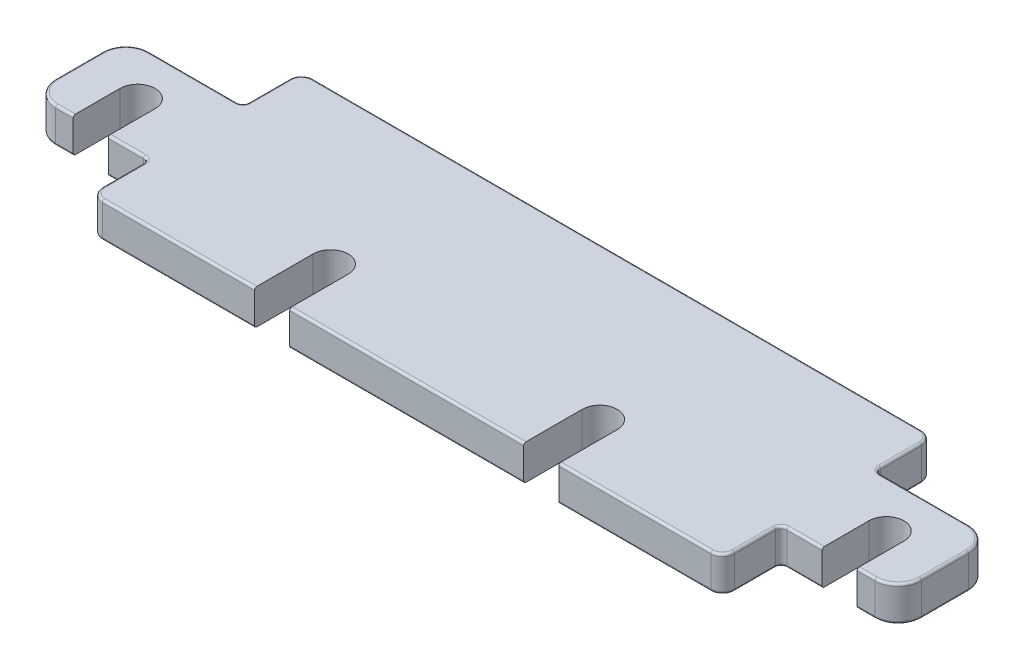
SolidWorks part; units mm, degrees
ref_plane "Front Plane" through (0, 0, 0) normal (0, 0, 1) x (1, 0, 0)
ref_plane "Top Plane" through (0, 0, 0) normal (0, 1, 0) x (1, 0, 0)
ref_plane "Right Plane" through (0, 0, 0) normal (1, 0, 0) x (0, 0, -1)
sketch "Sketch1" plane through (0, 0, 0) normal (0, 1, 0) x (1, 0, 0)
  line L0 (0, 0) -> (0, 18) construction
  line L1 (-10, 5) -> (-10, 0)
  line L2 (-10, 0) -> (10, 0)
  line L3 (-13, 5) -> (-13, 0)
  line L4 (-13, 0) -> (-26, 0)
  line L5 (-27, 1) -> (-27, 4.5)
  line L6 (-27.5, 5) -> (-30.5, 5)
  line L7 (-37, 7) -> (-37, 11)
  line L8 (-35, 13) -> (-27.5, 13)
  line L9 (-27, 13.5) -> (-27, 17)
  line L10 (-26, 18) -> (26, 18)
  line L11 (-33.5, 9) -> (-33.5, 5)
  line L12 (-30.5, 9) -> (-30.5, 5)
  line L13 (-33.5, 5) -> (-35, 5)
  line L14 (33.5, 5) -> (35, 5)
  line L15 (30.5, 9) -> (30.5, 5)
  line L16 (33.5, 9) -> (33.5, 5)
  line L17 (27, 13.5) -> (27, 17)
  line L18 (35, 13) -> (27.5, 13)
  line L19 (37, 7) -> (37, 11)
  line L20 (27.5, 5) -> (30.5, 5)
  line L21 (27, 1) -> (27, 4.5)
  line L22 (13, 0) -> (26, 0)
  line L23 (13, 5) -> (13, 0)
  line L24 (10, 5) -> (10, 0)
  arc A0 (-10, 5) -> (-13, 5) centre (-11.5, 5) ccw
  arc A1 (-30.5, 9) -> (-33.5, 9) centre (-32, 9) ccw
  arc A2 (-26, 0) -> (-27, 1) centre (-26, 1) cw
  arc A3 (-27, 17) -> (-26, 18) centre (-26, 17) cw
  arc A4 (-35, 5) -> (-37, 7) centre (-35, 7) cw
  arc A5 (-37, 11) -> (-35, 13) centre (-35, 11) cw
  arc A6 (-27, 4.5) -> (-27.5, 5) centre (-27.5, 4.5) ccw
  arc A7 (-27.5, 13) -> (-27, 13.5) centre (-27.5, 13.5) ccw
  arc A8 (27.5, 13) -> (27, 13.5) centre (27.5, 13.5) cw
  arc A9 (27, 4.5) -> (27.5, 5) centre (27.5, 4.5) cw
  arc A10 (37, 11) -> (35, 13) centre (35, 11) ccw
  arc A11 (35, 5) -> (37, 7) centre (35, 7) ccw
  arc A12 (27, 17) -> (26, 18) centre (26, 17) ccw
  arc A13 (26, 0) -> (27, 1) centre (26, 1) ccw
  arc A14 (30.5, 9) -> (33.5, 9) centre (32, 9) cw
  arc A15 (10, 5) -> (13, 5) centre (11.5, 5) cw
  point P21 (-27, 0)
  point P26 (-37, 5)
  point P29 (-37, 13)
  point P32 (-27, 5)
  point P63 (27, 5)
  point P64 (37, 13)
  point P65 (37, 5)
  point P66 (27, 0)
  dimension "D1" = 3
  dimension "D9" = 3
  dimension "D12" = 1
  dimension "D13" = 2
  dimension "D14" = 0.5
  dimension "D2" = 10
  dimension "D3" = 5
  dimension "D4" = 27
  dimension "D5" = 10
  dimension "D6" = 8
  dimension "D7" = 18
  dimension "D8" = 5
  dimension "D10" = 5
  dimension "D11" = 4
extrude "Boss-Extrude1" add sketch "Sketch1" along normal blind 3
fillet "Fillet1" radius 0.2 56 edges at (29, 0, -5) (27.1464, 0, -4.8536) (27, 0, -2.75) (26.7071, 0, -0.2929) (29, 3, -5) (27.1464, 3, -4.8536) (27, 3, -2.75) (26.7071, 3, -0.2929) (-29, 0, -5) (-27.1464, 0, -4.8536) (-27, 0, -2.75) (-26.7071, 0, -0.2929) (-19.5, 3, 0) (-26.7071, 3, -0.2929) (-27, 3, -2.75) (-27.1464, 3, -4.8536) (34.25, 0, -5) (36.4142, 0, -5.5858) (37, 0, -9) (36.4142, 0, -12.4142) (31.25, 0, -13) (27.1464, 0, -13.1464) (27, 0, -15.25) (26.7071, 0, -17.7071) (0, 0, -18) (-26.7071, 0, -17.7071) (-27, 0, -15.25) (-27.1464, 0, -13.1464) (-31.25, 0, -13) (-36.4142, 0, -12.4142) (-37, 0, -9) (-34.25, 0, -5) (34.25, 3, -5) (36.4142, 3, -5.5858) (37, 3, -9) (36.4142, 3, -12.4142) (31.25, 3, -13) (27.1464, 3, -13.1464) (27, 3, -15.25) (26.7071, 3, -17.7071) (0, 3, -18) (-26.7071, 3, -17.7071) (-27, 3, -15.25) (-27.1464, 3, -13.1464) (-31.25, 3, -13) (-36.4142, 3, -12.4142) (-37, 3, -9) (-34.25, 3, -5) (19.5, 0, 0) (19.5, 3, 0) (-19.5, 0, 0) (0, 0, 0) (0, 3, 0) (-29, 3, -5) (-36.4142, 0, -5.5858) (-36.4142, 3, -5.5858)
ref_plane "Plane1" through (0, 0, -9) normal (0, 0, 1) x (0, -1, 0)
ref_plane "Plane2" through (0, 0, -5) normal (0, 0, 1) x (0, -1, 0)
